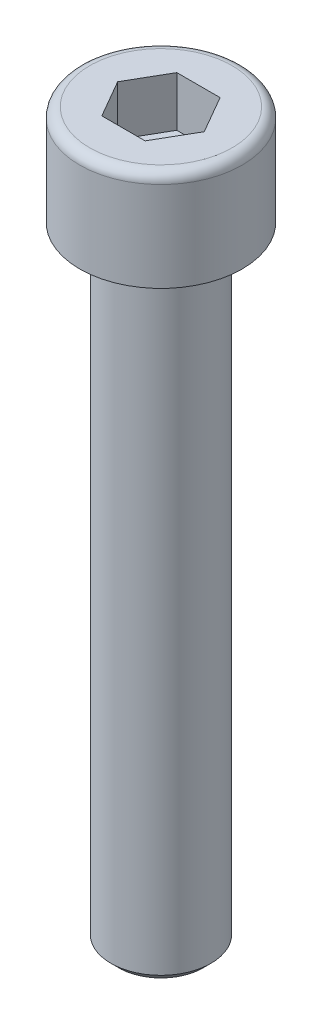
SolidWorks part; units mm, degrees
material "Plain Carbon Steel"
ref_plane "Front Plane" through (0, 0, 0) normal (0, 0, 1) x (1, 0, 0)
ref_plane "Top Plane" through (0, 0, 0) normal (0, 1, 0) x (1, 0, 0)
ref_plane "Right Plane" through (0, 0, 0) normal (1, 0, 0) x (0, 0, -1)
sketch "Sketch1" plane through (0, 0, 0) normal (0, 0, 1) x (1, 0, 0)
  line L0 (0, 0) -> (6.5, 0)
  line L1 (6.5, 0) -> (6.5, -8)
  line L2 (6.5, -8) -> (4, -8)
  line L3 (4, -8) -> (4, -58)
  line L4 (4, -58) -> (0, -58)
  line L5 (0, -58) -> (0, 0)
  line L6 (0, -63) -> (0, 5) construction
  dimension "D1" = 5
  dimension "D2" = 5
  dimension "H" = 8
  dimension "L" = 50
  dimension "D" = 8
  dimension "A" = 13
revolve "Revolve1" add sketch "Sketch1" angle 360 about L6
sketch "Sketch2" plane through (0, 0, 0) normal (0, 1, 0) x (1, 0, 0)
  line L7 (3.4641, 0) -> (1.7321, 3)
  line L8 (1.7321, 3) -> (-1.7321, 3)
  line L9 (-1.7321, 3) -> (-3.4641, 0)
  line L10 (-3.4641, 0) -> (-1.7321, -3)
  line L11 (-1.7321, -3) -> (1.7321, -3)
  line L12 (1.7321, -3) -> (3.4641, 0)
  circle A0 centre (0, 0) radius 3 construction
  dimension "D1" = 6
extrude "Cut-Extrude1" cut sketch "Sketch2" against normal blind 4
fillet "Fillet3" radius 0.8 1 edges at (0, 0, -6.5)
chamfer "Chamfer1" distance 0.625 angle 45 1 edges at (0, -58, -4)
cosmetic thread "Cosmetic Thread1" parameters "D1"=25, "D2"=6.619
ref_plane "ThreadStop" through (0, -11.75, 0) normal (0, -1, 0) x (-1, 0, 0)
fillet "Fillet4" [suppressed] radius 0.25
